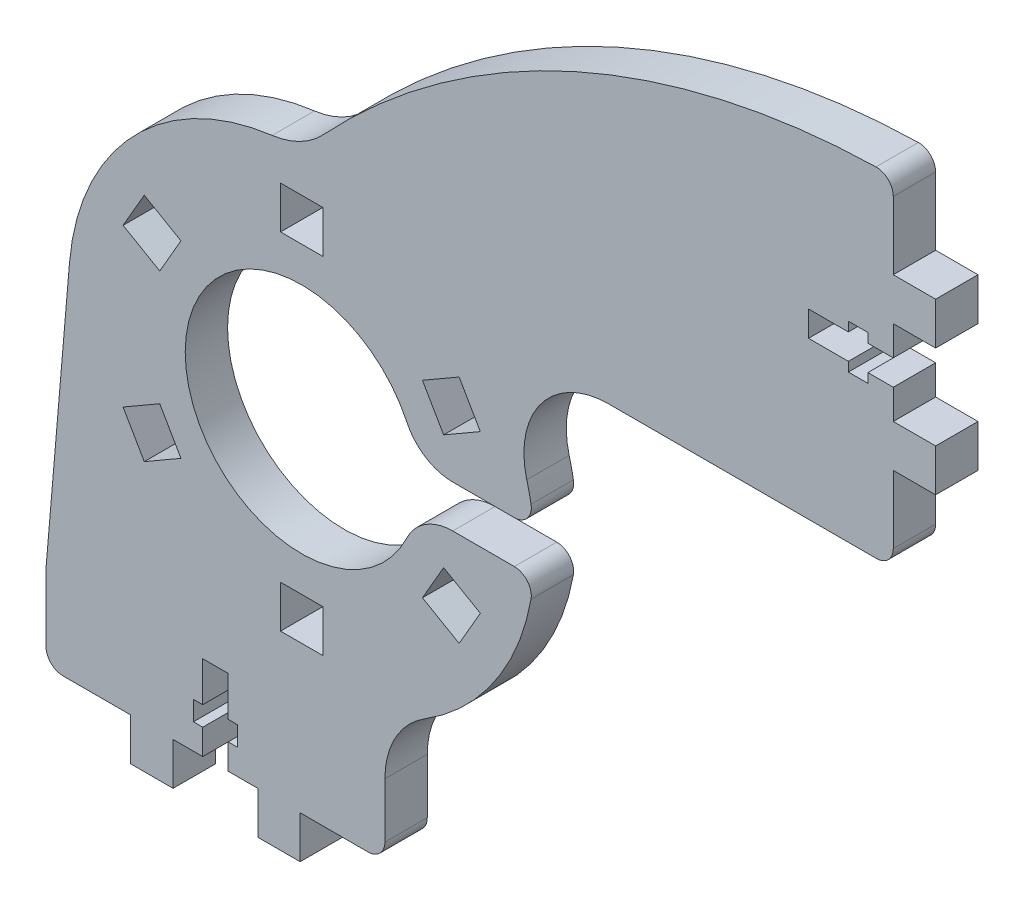
SolidWorks part; units mm, degrees
ref_plane "Plan de face" through (0, 0, 0) normal (0, 0, 1) x (1, 0, 0)
ref_plane "Plan de dessus" through (0, 0, 0) normal (0, 1, 0) x (1, 0, 0)
ref_plane "Plan de droite" through (0, 0, 0) normal (1, 0, 0) x (0, 0, -1)
sketch "Esquisse1" plane through (0, 0, 0) normal (0, 0, 1) x (1, 0, 0)
  line L0 (-62, 0) -> (-70, 0)
  line L1 (-70, 0) -> (-70, -5)
  line L2 (-70, -5) -> (-75, -5)
  line L3 (-75, -5) -> (-75, 0)
  line L4 (-78.5, 3) -> (-77.4, 3)
  line L5 (-77.4, 3) -> (-77.4, 5.3)
  line L6 (-77.4, 5.3) -> (-78.5, 5.3)
  line L7 (-78.5, 5.3) -> (-78.5, 10)
  line L8 (-78.5, 10) -> (-81.5, 10)
  line L9 (-81.5, 10) -> (-81.5, 5.3)
  line L10 (-81.5, 5.3) -> (-82.6, 5.3)
  line L11 (-82.6, 5.3) -> (-82.6, 3)
  line L12 (-82.6, 3) -> (-81.5, 3)
  line L13 (-75, 0) -> (-78.5, 0)
  line L14 (-85, -5) -> (-90, -5)
  line L15 (-90, -5) -> (-90, 0)
  line L16 (-90, 0) -> (-98, 0)
  line L17 (-100, 2) -> (-100, 10)
  line L18 (0, 100.0223) -> (-69.2197, 100.0223) construction
  line L19 (0, 98) -> (0, 90)
  line L20 (0, 90) -> (5, 90)
  line L21 (5, 90) -> (5, 85)
  line L22 (-78.5, 0) -> (-78.5, 3)
  line L23 (-3, 81.5) -> (-3, 82.6)
  line L24 (-3, 82.6) -> (-5.3, 82.6)
  line L25 (-5.3, 82.6) -> (-5.3, 81.5)
  line L26 (-5.3, 81.5) -> (-10, 81.5)
  line L27 (-10, 81.5) -> (-10, 78.5)
  line L28 (-10, 78.5) -> (-5.3, 78.5)
  line L29 (-5.3, 78.5) -> (-5.3, 77.4)
  line L30 (-5.3, 77.4) -> (-3, 77.4)
  line L31 (-3, 77.4) -> (-3, 78.5)
  line L32 (-85, -5) -> (-85, 0)
  line L33 (5, 75) -> (5, 70)
  line L34 (5, 70) -> (0, 70)
  line L35 (0, 70) -> (0, 62)
  line L36 (-85, 0) -> (-81.5, 0)
  line L37 (-81.5, 0) -> (-81.5, 3)
  line L38 (5, 75) -> (0, 75)
  line L39 (0, 75) -> (0, 78.5)
  line L40 (0, 78.5) -> (-3, 78.5)
  line L41 (5, 85) -> (0, 85)
  line L42 (0, 85) -> (0, 81.5)
  line L43 (0, 81.5) -> (-3, 81.5)
  line L44 (-69.8212, 58.2113) -> (-69.8212, 40.3113) construction
  line L45 (-72.3212, 63.2113) -> (-67.3212, 63.2113)
  line L46 (-72.3212, 63.2113) -> (-72.3212, 58.2113)
  line L47 (-72.3212, 58.2113) -> (-67.3212, 58.2113)
  line L48 (-67.3212, 63.2113) -> (-67.3212, 58.2113)
  line L49 (-51.2392, 53.9264) -> (-48.7392, 49.5962)
  line L50 (-51.2392, 53.9264) -> (-55.5693, 51.4264)
  line L51 (-55.5693, 51.4264) -> (-53.0693, 47.0962)
  line L52 (-48.7392, 49.5962) -> (-53.0693, 47.0962)
  line L53 (-48.7392, 31.0264) -> (-51.2392, 26.6962)
  line L54 (-48.7392, 31.0264) -> (-53.0693, 33.5264)
  line L55 (-53.0693, 33.5264) -> (-55.5693, 29.1962)
  line L56 (-51.2392, 26.6962) -> (-55.5693, 29.1962)
  line L57 (-67.3212, 17.4113) -> (-72.3212, 17.4113)
  line L58 (-67.3212, 17.4113) -> (-67.3212, 22.4113)
  line L59 (-67.3212, 22.4113) -> (-72.3212, 22.4113)
  line L60 (-72.3212, 17.4113) -> (-72.3212, 22.4113)
  line L61 (-88.4032, 26.6962) -> (-90.9032, 31.0264)
  line L62 (-88.4032, 26.6962) -> (-84.0731, 29.1962)
  line L63 (-84.0731, 29.1962) -> (-86.5731, 33.5264)
  line L64 (-90.9032, 31.0264) -> (-86.5731, 33.5264)
  line L65 (-90.9032, 49.5962) -> (-88.4032, 53.9264)
  line L66 (-90.9032, 49.5962) -> (-86.5731, 47.0962)
  line L67 (-86.5731, 47.0962) -> (-84.0731, 51.4264)
  line L68 (-88.4032, 53.9264) -> (-84.0731, 51.4264)
  line L69 (-69.8212, 40.3113) -> (0, 0) construction
  line L70 (-44.7214, 42.8113) -> (-51.9939, 42.8113)
  line L71 (-51.9939, 37.8113) -> (-44.7214, 37.8113)
  line L72 (-60, 2) -> (-60, 8.4778)
  line L73 (-45, 0) -> (0, 0) construction
  line L74 (-100, 10) -> (-97.2222, 42.643)
  line L75 (-2, 60) -> (-33.5944, 60)
  arc A0 (-80, 10) -> (-10, 80) centre (0, 0) cw construction
  arc A1 (-57.4098, 46.229) -> (-57.4098, 34.3936) centre (-69.8212, 40.3113) ccw
  arc A2 (-51.9939, 37.8113) -> (-57.4098, 34.3936) centre (-51.9939, 31.8113) ccw
  arc A3 (-51.9939, 42.8113) -> (-57.4098, 46.229) centre (-51.9939, 48.8113) cw
  arc A4 (-55.2857, 16.9667) -> (-42.7528, 35.4583) centre (-69.8212, 40.3113) ccw
  arc A5 (-2.0446, 99.9995) -> (-67.2464, 70.7035) centre (0, 8.2439) ccw
  arc A6 (-73.3062, 67.5896) -> (-97.2222, 42.643) centre (-69.8212, 40.3113) ccw
  arc A7 (-60, 8.4778) -> (-55.2857, 16.9667) centre (-50, 8.4778) cw
  arc A8 (-33.5944, 60) -> (-43.2549, 47.4163) centre (-33.5944, 50) ccw
  arc A9 (-67.2464, 70.7035) -> (-73.3062, 67.5896) centre (-74.5734, 77.509) cw
  arc A10 (-2.0446, 99.9995) -> (0, 98) centre (-2, 98) cw
  arc A11 (0, 62) -> (-2, 60) centre (-2, 62) cw
  arc A12 (-98, 0) -> (-100, 2) centre (-98, 2) cw
  arc A13 (-62, 0) -> (-60, 2) centre (-62, 2) ccw
  arc A14 (-42.7528, 45.1642) -> (-43.2549, 47.4163) centre (-69.8212, 40.3113) ccw
  arc A15 (-44.7214, 37.8113) -> (-42.7528, 35.4583) centre (-44.7214, 35.8113) cw
  arc A16 (-44.7214, 42.8113) -> (-42.7528, 45.1642) centre (-44.7214, 44.8113) ccw
  point P51 (-80, 10)
  point P53 (-10, 80)
  point P82 (-69.8212, 40.3113)
  point P95 (-69.8212, 67.8113)
  point P104 (0, 60)
  point P108 (-100, 0)
  point P111 (-60, 0)
  point P116 (-42.4351, 42.8113)
  dimension "D1" = 5
  dimension "D9" = 100
  dimension "D10" = 27.5
  dimension "D17" = 6
  dimension "D18" = 55
  dimension "D19" = 10
  dimension "D21" = 10
  dimension "D22" = 10
  dimension "D23" = 2
  dimension "D24" = 2
  dimension "D2" = 5
  dimension "D3" = 2.3
  dimension "D4" = 3
  dimension "D5" = 3
  dimension "D6" = 4.7
  dimension "D7" = 1.1
  dimension "D8" = 3.5
  dimension "D11" = 17.9
  dimension "D12" = 5
  dimension "D13" = 6
  dimension "D14" = 30
  dimension "D15" = 5
  dimension "D16" = 2.5
  dimension "D20" = 10
extrude "Boss.-Extru.1" add sketch "Esquisse1" along normal blind 5
